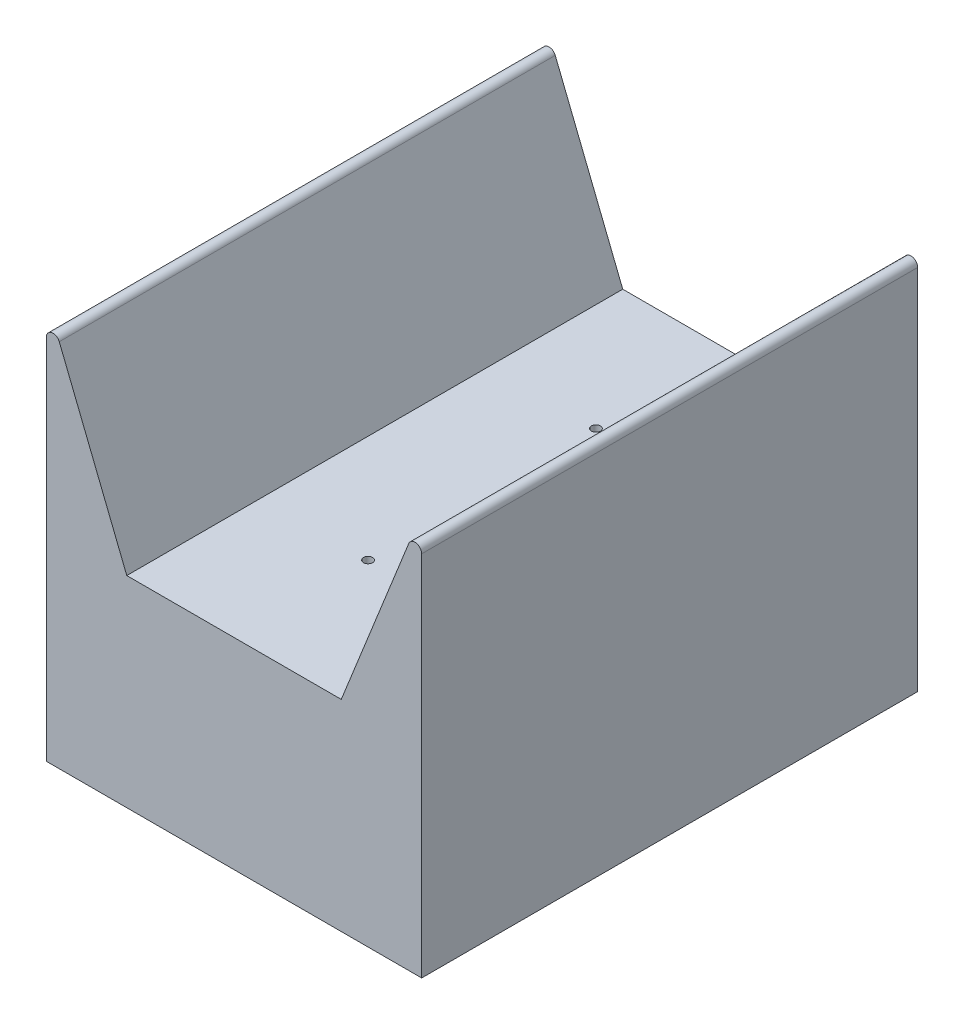
SolidWorks part; units mm, degrees
ref_plane "Plan de face" through (0, 0, 0) normal (0, 0, 1) x (1, 0, 0)
ref_plane "Plan de dessus" through (0, 0, 0) normal (0, 1, 0) x (1, 0, 0)
ref_plane "Plan de droite" through (0, 0, 0) normal (1, 0, 0) x (0, 0, -1)
sketch "Esquisse1" plane through (0, 0, 0) normal (0, 1, 0) x (1, 0, 0)
  line L0 (-12, 18.5) -> (-14, 18.5)
  line L1 (-12, -18.5) -> (12, -18.5)
  line L2 (-12, -18.5) -> (-12, 18.5)
  line L3 (-12, 18.5) -> (12, 18.5)
  line L4 (12, -18.5) -> (12, 18.5)
  line L5 (-12, -18.5) -> (12, 18.5) construction
  line L6 (-12, 18.5) -> (12, -18.5) construction
  line L7 (-14, 18.5) -> (-14, -18.5)
  line L8 (-14, -18.5) -> (-12, -18.5)
  line L9 (12, 18.5) -> (14, 18.5)
  line L10 (14, 18.5) -> (14, -18.5)
  line L11 (14, -18.5) -> (12, -18.5)
  point P0 (0, 0)
  dimension "D1" = 37
  dimension "D2" = 24
  dimension "D3" = 2
  dimension "D4" = 2
extrude "Boss.-Extru.1" add sketch "Esquisse1" along normal blind 30 contours L7 L8 L2 L0 | L1 L4 L3 L2 | L11 L10 L9 L4
sketch "Esquisse3" plane through (0, 0, -18.5) normal (0, 0, -1) x (-1, 0, 0)
  line L0 (14, 0) -> (14, 15)
  line L1 (14, 30) -> (14, 0) construction
  line L2 (14, 15) -> (-14, 15)
  line L3 (-14, 30) -> (-14, 0) construction
  line L4 (-8, 15) -> (-14, 30)
  line L5 (-14, 30) -> (14, 30) construction
  line L6 (8, 15) -> (14, 30)
  line L7 (14, 15) -> (14, 30)
  dimension "D1" = 6
  dimension "D2" = 6
extrude "Enlèv. mat.-Extru.3" cut sketch "Esquisse3" against normal blind 40 contours L2 L6 L4
fillet "Congé1" radius 0.5 2 edges at (-14, 30, 0) (14, 30, 0)
sketch "Esquisse4" plane through (0, 15, 0) normal (0, 1, 0) x (1, 0, 0)
  line L0 (-8, -18.5) -> (8, -18.5) construction
  line L1 (-8, 18.5) -> (8, 18.5) construction
  circle A0 centre (0, 8.5) radius 0.34
  circle A1 centre (0, -8.5) radius 0.34
  dimension "D1" = 0.68
  dimension "D2" = 0.68
  dimension "D4" = 10
  dimension "D3" = 10
extrude "Enlèv. mat.-Extru.4" cut sketch "Esquisse4" against normal blind 12
sketch "Esquisse5" plane through (-14, 0, 0) normal (-1, 0, 0) x (0, 0, 1)
  line L0 (-18.5, 0) -> (18.5, 0) construction
  line L1 (18.5, 27.4037) -> (18.5, 0) construction
  line L2 (-18.5, 27.4037) -> (-18.5, 0) construction
  circle A0 centre (-8.5, 3) radius 1.5
  circle A1 centre (8.5, 3) radius 1.5
  dimension "D1" = 3
  dimension "D2" = 3
  dimension "D3" = 3
  dimension "D4" = 10
  dimension "D5" = 3
  dimension "D6" = 10
extrude "Enlèv. mat.-Extru.6" cut sketch "Esquisse5" against normal blind 16
